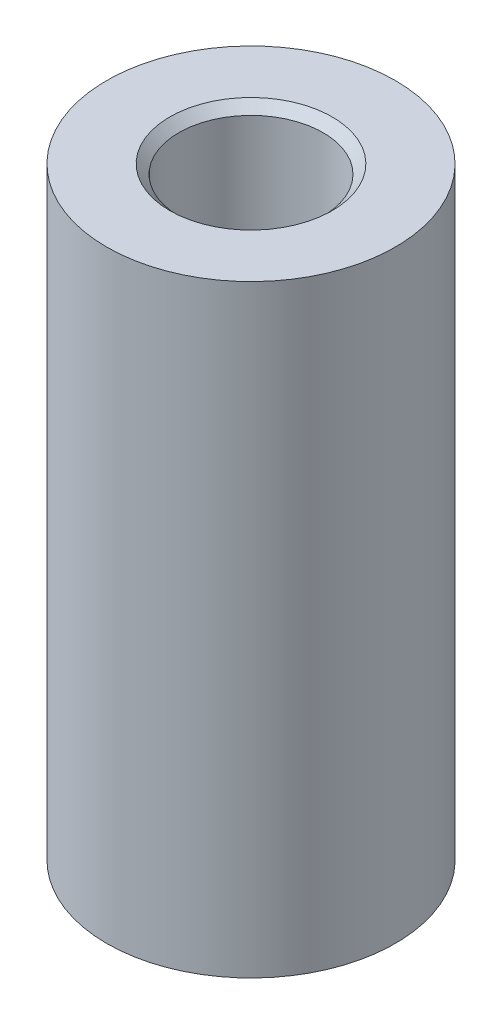
SolidWorks part; units mm, degrees
ref_plane "Front Plane" through (0, 0, 0) normal (0, 0, 1) x (1, 0, 0)
ref_plane "Top Plane" through (0, 0, 0) normal (0, 1, 0) x (1, 0, 0)
ref_plane "Right Plane" through (0, 0, 0) normal (1, 0, 0) x (0, 0, -1)
sketch "Sketch1" plane through (0, 0, 0) normal (0, 1, 0) x (1, 0, 0)
  circle A0 centre (0, 0) radius 3.175
  circle A1 centre (0, 0) radius 6.35
  dimension "D1" = 6.35
  dimension "D2" = 3.175
extrude "Boss-Extrude1" add sketch "Sketch1" along normal blind 26.543
chamfer "Chamfer1" distance 0.4 angle 45 2 edges at (0, 0, 3.175) (0, 26.543, 3.175)
